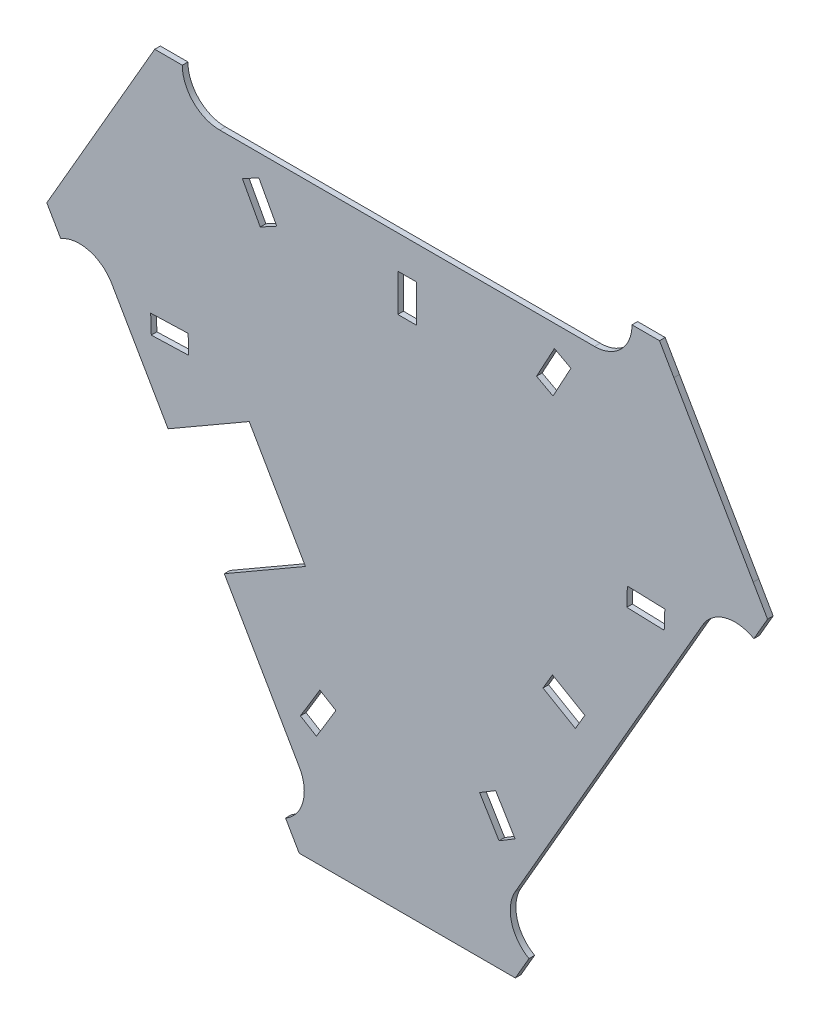
SolidWorks part; units mm, degrees
ref_plane "Plan de face" through (0, 0, 0) normal (0, 0, 1) x (1, 0, 0)
ref_plane "Plan de dessus" through (0, 0, 0) normal (0, 1, 0) x (1, 0, 0)
ref_plane "Plan de droite" through (0, 0, 0) normal (1, 0, 0) x (0, 0, -1)
sketch "Model" plane through (0, 0, 0) normal (0, 0, 1) x (1, 0, 0)
  line L662 (118.6164, -1154.7177) -> (127.9304, -1137.5509)
  line L663 (127.9304, -1137.5509) -> (136.72, -1142.3198)
  line L664 (136.72, -1142.3198) -> (127.5618, -1159.1996)
  line L665 (144.7752, -1191.5513) -> (166.7752, -1191.5513)
  line L666 (200.7752, -1152.8693) -> (200.7752, -1133.8449)
  line L667 (200.7752, -1133.8449) -> (210.7753, -1133.8449)
  line L668 (210.7753, -1133.8449) -> (210.7753, -1152.8693)
  line L669 (244.7753, -1191.5513) -> (266.7753, -1191.5513)
  line L670 (284.3929, -1158.9336) -> (275.3788, -1142.3198)
  line L671 (275.3788, -1142.3198) -> (284.1684, -1137.5509)
  line L672 (284.1684, -1137.5509) -> (293.3961, -1154.5585)
  line L673 (344.2368, -1185.0738) -> (354.3495, -1167.558)
  line L674 (354.3495, -1167.558) -> (328.3719, -1152.5598)
  line L675 (328.3719, -1152.5598) -> (333.1301, -1144.3183)
  line L676 (333.1301, -1144.3183) -> (264.2714, -1104.2143)
  line L677 (264.2714, -1104.2143) -> (284.3684, -1069.0978)
  line L678 (284.3684, -1069.0978) -> (353.3599, -1109.2793)
  line L679 (353.3599, -1109.2793) -> (358.3718, -1100.5983)
  line L680 (358.3718, -1100.5983) -> (384.3494, -1115.5964)
  line L681 (384.3494, -1115.5964) -> (394.4221, -1098.1497)
  line L682 (342.2811, -1068.5144) -> (322.6668, -1069.1396)
  line L683 (322.6668, -1069.1396) -> (322.3483, -1059.1447)
  line L684 (322.3483, -1059.1447) -> (341.8054, -1058.5245)
  line L685 (361.1808, -1027.8726) -> (350.1807, -1008.82)
  line L686 (299.413, -998.3554) -> (282.7063, -1008.1211)
  line L687 (282.7063, -1008.1211) -> (277.6598, -999.4879)
  line L688 (277.6598, -999.4879) -> (294.5118, -989.6372)
  line L689 (311.1809, -941.27) -> (300.1809, -922.2175)
  line L690 (262.3971, -922.8937) -> (252.3743, -939.4373)
  line L691 (252.3743, -939.4373) -> (243.8215, -934.2556)
  line L692 (243.8215, -934.2556) -> (254.1849, -917.15)
  line L693 (254.1849, -917.15) -> (254.439, -917.3039)
  line L694 (255.6733, -858.5099) -> (247.9625, -858.5099)
  line L695 (247.9625, -858.5099) -> (235.7176, -858.5099)
  line L696 (235.7176, -858.5099) -> (235.7176, -888.5099)
  line L697 (235.7176, -888.5099) -> (225.7175, -888.5099)
  line L698 (225.7175, -888.5099) -> (225.7175, -968.5099)
  line L699 (225.7175, -968.5099) -> (185.7176, -968.5099)
  line L700 (185.7176, -968.5099) -> (185.7176, -888.5099)
  line L701 (185.7176, -888.5099) -> (175.7175, -888.5099)
  line L702 (175.7175, -888.5099) -> (175.7175, -858.5099)
  line L703 (175.7175, -858.5099) -> (163.4726, -858.5099)
  line L704 (163.4726, -858.5099) -> (155.7618, -858.5099)
  line L705 (156.5681, -917.6896) -> (156.7309, -917.591)
  line L706 (156.7309, -917.591) -> (167.0942, -934.6965)
  line L707 (167.0942, -934.6965) -> (158.5415, -939.8782)
  line L708 (158.5415, -939.8782) -> (148.4396, -923.2044)
  line L709 (111.2542, -922.2175) -> (100.2542, -941.27)
  line L710 (116.676, -990.2373) -> (133.2558, -999.9289)
  line L711 (133.2558, -999.9289) -> (128.2093, -1008.5621)
  line L712 (128.2093, -1008.5621) -> (111.6322, -998.8721)
  line L713 (61.2542, -1008.82) -> (50.2542, -1027.8726)
  line L714 (69.6666, -1058.9832) -> (88.5674, -1059.5857)
  line L715 (88.5674, -1059.5857) -> (88.2488, -1069.5806)
  line L716 (88.2488, -1069.5806) -> (69.0689, -1068.9692)
  line L717 (17.2057, -1098.2221) -> (21.0894, -1104.9488)
  line L718 (21.0894, -1104.9488) -> (27.2432, -1115.6074)
  line L719 (27.2432, -1115.6074) -> (53.2397, -1100.5983)
  line L720 (53.2397, -1100.5983) -> (58.2396, -1109.2586)
  line L721 (58.2396, -1109.2586) -> (127.5216, -1069.2586)
  line L722 (127.5216, -1069.2586) -> (147.5216, -1103.8996)
  line L723 (147.5216, -1103.8996) -> (78.2396, -1143.8996)
  line L724 (78.2396, -1143.8996) -> (83.2396, -1152.5598)
  line L725 (83.2396, -1152.5598) -> (57.2432, -1167.5689)
  line L726 (57.2432, -1167.5689) -> (63.4324, -1178.2888)
  line L727 (63.4324, -1178.2888) -> (63.4324, -1178.289)
  line L728 (63.4324, -1178.289) -> (67.3217, -1185.0257)
  line L729 (347.5042, -990.9847) -> (447.5042, -1164.1898)
  line L730 (440.1849, -1191.5058) -> (447.4682, -1204.1207)
  line L731 (447.4682, -1204.1207) -> (462.9049, -1204.1207)
  line L732 (462.9049, -1204.1207) -> (547.3949, -1204.1207)
  line L733 (547.3949, -1204.1207) -> (562.8317, -1204.1207)
  line L734 (562.8317, -1204.1207) -> (570.1149, -1191.5058)
  line L735 (562.7957, -1164.1898) -> (662.7956, -990.9847)
  line L736 (690.1116, -983.6655) -> (697.4457, -970.9625)
  line L737 (697.4457, -970.9625) -> (689.7781, -957.6819)
  line L738 (689.7781, -957.6819) -> (647.4351, -884.3418)
  line L739 (647.4351, -884.3418) -> (647.4351, -884.3416)
  line L740 (647.4351, -884.3416) -> (639.7782, -871.0793)
  line L741 (639.7782, -871.0793) -> (625.0923, -871.0793)
  line L742 (605.0923, -891.0793) -> (405.0923, -891.0793)
  line L743 (385.0923, -871.0793) -> (370.3705, -871.0793)
  line L744 (370.3705, -871.0793) -> (312.7787, -970.8316)
  line L745 (312.7787, -970.8316) -> (320.1882, -983.6655)
  line L1029 (622.6187, -993.0501) -> (642.6085, -993.6872)
  line L1030 (642.6085, -993.6872) -> (642.29, -1003.6822)
  line L1031 (642.29, -1003.6822) -> (622.3, -1003.045)
  line L1032 (622.3, -1003.045) -> (622.6187, -993.0501)
  line L1033 (594.8781, -1072.7947) -> (577.6116, -1062.7018)
  line L1034 (577.6116, -1062.7018) -> (582.6582, -1054.0686)
  line L1035 (582.6582, -1054.0686) -> (599.9247, -1064.1615)
  line L1036 (599.9247, -1064.1615) -> (594.8781, -1072.7947)
  line L1037 (583.6852, -902.7316) -> (592.4748, -907.5005)
  line L1038 (592.4748, -907.5005) -> (582.9371, -925.0797)
  line L1039 (582.9371, -925.0797) -> (574.1474, -920.3108)
  line L1040 (574.1474, -920.3108) -> (583.6852, -902.7316)
  line L1041 (552.326, -1122.7524) -> (562.6894, -1139.858)
  line L1042 (562.6894, -1139.858) -> (554.1366, -1145.0397)
  line L1043 (554.1366, -1145.0397) -> (543.7732, -1127.9341)
  line L1044 (543.7732, -1127.9341) -> (552.326, -1122.7524)
  line L1045 (500.0922, -908.7858) -> (510.0922, -908.7858)
  line L1046 (510.0922, -908.7858) -> (510.0922, -928.7858)
  line L1047 (510.0922, -928.7858) -> (500.0922, -928.7858)
  line L1048 (500.0922, -928.7858) -> (500.0922, -908.7858)
  line L1049 (458.4931, -1123.1934) -> (467.0459, -1128.3751)
  line L1050 (467.0459, -1128.3751) -> (456.6826, -1145.4807)
  line L1051 (456.6826, -1145.4807) -> (448.1298, -1140.299)
  line L1052 (448.1298, -1140.299) -> (458.4931, -1123.1934)
  line L1053 (425.9509, -902.7316) -> (435.4887, -920.3108)
  line L1054 (435.4887, -920.3108) -> (426.6991, -925.0797)
  line L1055 (426.6991, -925.0797) -> (417.1613, -907.5005)
  line L1056 (417.1613, -907.5005) -> (425.9509, -902.7316)
  line L1057 (428.1611, -1054.5095) -> (433.2077, -1063.1428)
  line L1058 (433.2077, -1063.1428) -> (415.9412, -1073.2357)
  line L1059 (415.9412, -1073.2357) -> (410.8947, -1064.6025)
  line L1060 (410.8947, -1064.6025) -> (428.1611, -1054.5095)
  line L1061 (388.2006, -993.4911) -> (388.5191, -1003.486)
  line L1062 (388.5191, -1003.486) -> (368.5293, -1004.1231)
  line L1063 (368.5293, -1004.1231) -> (368.2108, -994.1282)
  line L1064 (368.2108, -994.1282) -> (388.2006, -993.4911)
  spline S707 degree 3 poles (67.3217, -1185.0257) (70.4273, -1166.5936) (86.4601, -1152.5513) (105.7752, -1152.5513) knots 0 0 0 0 1 1 1 1
  spline S708 degree 3 poles (105.7752, -1152.5513) (110.2746, -1152.5513) (114.595, -1153.3158) (118.6164, -1154.7177) knots 1 1 1 1 2 2 2 2
  spline S709 degree 3 poles (127.5618, -1159.1996) (137.9463, -1166.2065) (144.7752, -1178.0813) (144.7752, -1191.5513) knots 5 5 5 5 6 6 6 6
  spline S710 degree 3 poles (166.7752, -1191.5513) (166.7752, -1171.7063) (181.5976, -1155.3237) (200.7752, -1152.8693) knots 7 7 7 7 8 8 8 8
  spline S711 degree 3 poles (210.7753, -1152.8693) (229.9529, -1155.3237) (244.7753, -1171.7063) (244.7753, -1191.5513) knots 11 11 11 11 12 12 12 12
  spline S712 degree 3 poles (266.7753, -1191.5513) (266.7753, -1177.9081) (273.7825, -1165.9033) (284.3929, -1158.9336) knots 13 13 13 13 14 14 14 14
  spline S713 degree 3 poles (293.3961, -1154.5585) (297.2856, -1153.2575) (301.4478, -1152.5513) (305.7752, -1152.5513) knots 17 17 17 17 18 18 18 18
  spline S714 degree 3 poles (305.7752, -1152.5513) (325.1072, -1152.5513) (341.151, -1166.6181) (344.2368, -1185.0738) knots 18 18 18 18 19 19 19 19
  spline S715 degree 3 poles (394.4221, -1098.1497) (376.8685, -1104.7819) (356.594, -1097.9278) (346.9058, -1081.1476) knots 28 28 28 28 29 29 29 29
  spline S716 degree 3 poles (346.9058, -1081.1476) (344.5792, -1077.1177) (343.0553, -1072.8451) (342.2811, -1068.5144) knots 29 29 29 29 30 30 30 30
  spline S717 degree 3 poles (341.8054, -1058.5245) (342.8076, -1046.187) (349.6499, -1034.53) (361.1808, -1027.8726) knots 33 33 33 33 34 34 34 34
  spline S718 degree 3 poles (350.1807, -1008.82) (332.8616, -1018.8192) (311.0631, -1014.0226) (299.413, -998.3554) knots 35 35 35 35 36 36 36 36
  spline S719 degree 3 poles (294.5118, -989.6372) (287.327, -971.8923) (294.1287, -951.1151) (311.1809, -941.27) knots 39 39 39 39 40 40 40 40
  spline S720 degree 3 poles (300.1809, -922.2175) (288.1117, -929.1856) (273.8672, -928.9671) (262.3971, -922.8937) knots 43 43 43 43 44 44 44 44
  spline S721 degree 3 poles (254.439, -917.3039) (251.5315, -914.6591) (248.9762, -911.5284) (246.9059, -907.9425) knots 48 48 48 48 49 49 49 49
  spline S722 degree 3 poles (246.9059, -907.9425) (237.277, -891.265) (241.3676, -870.4333) (255.6733, -858.5099) knots 49 49 49 49 50 50 50 50
  spline S723 degree 3 poles (155.7618, -858.5099) (170.0675, -870.4333) (174.1581, -891.265) (164.5292, -907.9425) knots 61 61 61 61 62 62 62 62
  spline S724 degree 3 poles (164.5292, -907.9425) (162.3578, -911.7037) (159.6535, -914.9655) (156.5681, -917.6896) knots 62 62 62 62 63 63 63 63
  spline S725 degree 3 poles (148.4396, -923.2044) (137.0752, -928.9728) (123.1145, -929.0649) (111.2542, -922.2175) knots 67 67 67 67 68 68 68 68
  spline S726 degree 3 poles (100.2542, -941.27) (117.499, -951.2262) (124.2617, -972.3631) (116.676, -990.2373) knots 71 71 71 71 72 72 72 72
  spline S727 degree 3 poles (111.6322, -998.8721) (99.8908, -1014.1275) (78.3818, -1018.7086) (61.2542, -1008.82) knots 75 75 75 75 76 76 76 76
  spline S728 degree 3 poles (50.2542, -1027.8726) (61.9282, -1034.6125) (68.7988, -1046.4764) (69.6666, -1058.9832) knots 79 79 79 79 80 80 80 80
  spline S729 degree 3 poles (69.0689, -1068.9692) (68.271, -1073.1441) (66.7744, -1077.2589) (64.5293, -1081.1476) knots 83 83 83 83 84 84 84 84
  spline S730 degree 3 poles (64.5293, -1081.1476) (54.8766, -1097.8664) (34.7149, -1104.7317) (17.2057, -1098.2221) knots 84 84 84 84 85 85 85 85
  spline S731 degree 3 poles (345.1602, -1171.4403) (344.2035, -1170.888) (343.8759, -1169.6648) (344.4281, -1168.7083) knots 3 3 3 3 4 4 4 4
  spline S732 degree 3 poles (347.8922, -1170.7082) (347.3399, -1171.6649) (346.1167, -1171.9926) (345.1602, -1171.4403) knots 2 2 2 2 3 3 3 3
  spline S733 degree 3 poles (347.1603, -1167.9762) (348.1168, -1168.5285) (348.4446, -1169.7517) (347.8922, -1170.7082) knots 1 1 1 1 2 2 2 2
  spline S734 degree 3 poles (344.4281, -1168.7083) (344.9804, -1167.7517) (346.2036, -1167.4239) (347.1603, -1167.9762) knots 0 0 0 0 1 1 1 1
  spline S735 degree 3 poles (381.117, -1109.1613) (380.1603, -1108.609) (379.8327, -1107.3858) (380.3849, -1106.4292) knots 3 3 3 3 4 4 4 4
  spline S736 degree 3 poles (383.849, -1108.4293) (383.2967, -1109.3858) (382.0735, -1109.7136) (381.117, -1109.1613) knots 2 2 2 2 3 3 3 3
  spline S737 degree 3 poles (383.1169, -1105.6972) (384.0736, -1106.2495) (384.4012, -1107.4727) (383.849, -1108.4293) knots 1 1 1 1 2 2 2 2
  spline S738 degree 3 poles (380.3849, -1106.4292) (380.9372, -1105.4727) (382.1604, -1105.1449) (383.1169, -1105.6972) knots 0 0 0 0 1 1 1 1
  spline S739 degree 3 poles (241.6744, -866.5305) (240.5699, -866.5305) (239.6743, -865.6351) (239.6743, -864.5305) (239.6743, -863.426) (240.5699, -862.5305) (241.6744, -862.5305) knots 2 2 2 2 3 3 3 4 4 4 4
  spline S740 degree 3 poles (241.6744, -862.5305) (242.7789, -862.5305) (243.6744, -863.426) (243.6744, -864.5305) (243.6744, -865.6351) (242.7789, -866.5305) (241.6744, -866.5305) knots 0 0 0 0 1 1 1 2 2 2 2
  spline S741 degree 3 poles (171.7608, -864.5305) (171.7608, -865.6351) (170.8653, -866.5305) (169.7608, -866.5305) (168.6563, -866.5305) (167.7607, -865.6351) (167.7607, -864.5305) knots 2 2 2 2 3 3 3 4 4 4 4
  spline S742 degree 3 poles (167.7607, -864.5305) (167.7607, -863.426) (168.6563, -862.5305) (169.7608, -862.5305) (170.8653, -862.5305) (171.7608, -863.426) (171.7608, -864.5305) knots 0 0 0 0 1 1 1 2 2 2 2
  spline S743 degree 3 poles (31.2266, -1106.4292) (31.7788, -1107.3858) (31.4512, -1108.609) (30.4945, -1109.1613) knots 3 3 3 3 4 4 4 4
  spline S744 degree 3 poles (28.4944, -1105.6972) (29.4511, -1105.1449) (30.6743, -1105.4727) (31.2266, -1106.4292) knots 2 2 2 2 3 3 3 3
  spline S745 degree 3 poles (27.7625, -1108.4293) (27.2101, -1107.4727) (27.5379, -1106.2495) (28.4944, -1105.6972) knots 1 1 1 1 2 2 2 2
  spline S746 degree 3 poles (30.4945, -1109.1613) (29.538, -1109.7136) (28.3148, -1109.3858) (27.7625, -1108.4293) knots 0 0 0 0 1 1 1 1
  spline S747 degree 3 poles (63.7193, -1170.7082) (63.1669, -1169.7517) (63.4947, -1168.5285) (64.4512, -1167.9762) knots 3 3 3 3 4 4 4 4
  spline S748 degree 3 poles (66.4513, -1171.4403) (65.4948, -1171.9926) (64.2716, -1171.6649) (63.7193, -1170.7082) knots 2 2 2 2 3 3 3 3
  spline S749 degree 3 poles (67.1834, -1168.7083) (67.7356, -1169.6648) (67.4078, -1170.888) (66.4513, -1171.4403) knots 1 1 1 1 2 2 2 2
  spline S750 degree 3 poles (64.4512, -1167.9762) (65.4079, -1167.4239) (66.6311, -1167.7517) (67.1834, -1168.7083) knots 0 0 0 0 1 1 1 1
  spline S751 degree 3 poles (447.5042, -1164.1898) (453.0261, -1173.7541) (449.7492, -1185.9838) (440.1849, -1191.5058) knots 1 1 1 1 2 2 2 2
  spline S752 degree 3 poles (570.1149, -1191.5058) (560.5507, -1185.9838) (557.2737, -1173.7541) (562.7957, -1164.1898) knots 7 7 7 7 8 8 8 8
  spline S753 degree 3 poles (662.7956, -990.9847) (668.3175, -981.4205) (680.5473, -978.1436) (690.1116, -983.6655) knots 9 9 9 9 10 10 10 10
  spline S754 degree 3 poles (625.0923, -871.0793) (625.0923, -882.125) (616.138, -891.0793) (605.0923, -891.0793) knots 17 17 17 17 18 18 18 18
  spline S755 degree 3 poles (405.0923, -891.0793) (394.0466, -891.0793) (385.0923, -882.125) (385.0923, -871.0793) knots 19 19 19 19 20 20 20 20
  spline S756 degree 3 poles (320.1882, -983.6655) (329.7525, -978.1435) (341.9823, -981.4205) (347.5042, -990.9847) knots 23 23 23 23 24 24 24 24
extrude "Boss.-Extru.1" add sketch "Model" along normal blind 3 contours L745 S756 L729 S751 L730 L731 L732 L733 L734 S752 L735 S753 L736 L737 L738 L739 L740 L741 S754 L742 S755 L743 L744 L1063 L1064 L1061 L1062 L1059 L1060 L1057 L1058 L1055 L1056 L1053 L1054 L1051 L1052 L1049 L1050 L1047 L1048 L1045 L1046 L1043 L1044
sketch "Esquisse2" plane through (0, 0, 3) normal (0, 0, 1) x (1, 0, 0)
  line L0 (377.5042, -1042.9463) -> (407.5042, -1094.9078)
  line L1 (377.5042, -1042.9463) -> (420.8055, -1017.9463)
  line L2 (407.5042, -1094.9078) -> (450.8055, -1069.9078)
  line L3 (420.8055, -1017.9463) -> (450.8055, -1069.9078)
  line L4 (347.5042, -990.9847) -> (447.5042, -1164.1898) construction
  dimension "D1" = 60
  dimension "D2" = 50
  dimension "D3" = 60
extrude "Enlèv. mat.-Extru.1" cut sketch "Esquisse2" against normal blind 10
